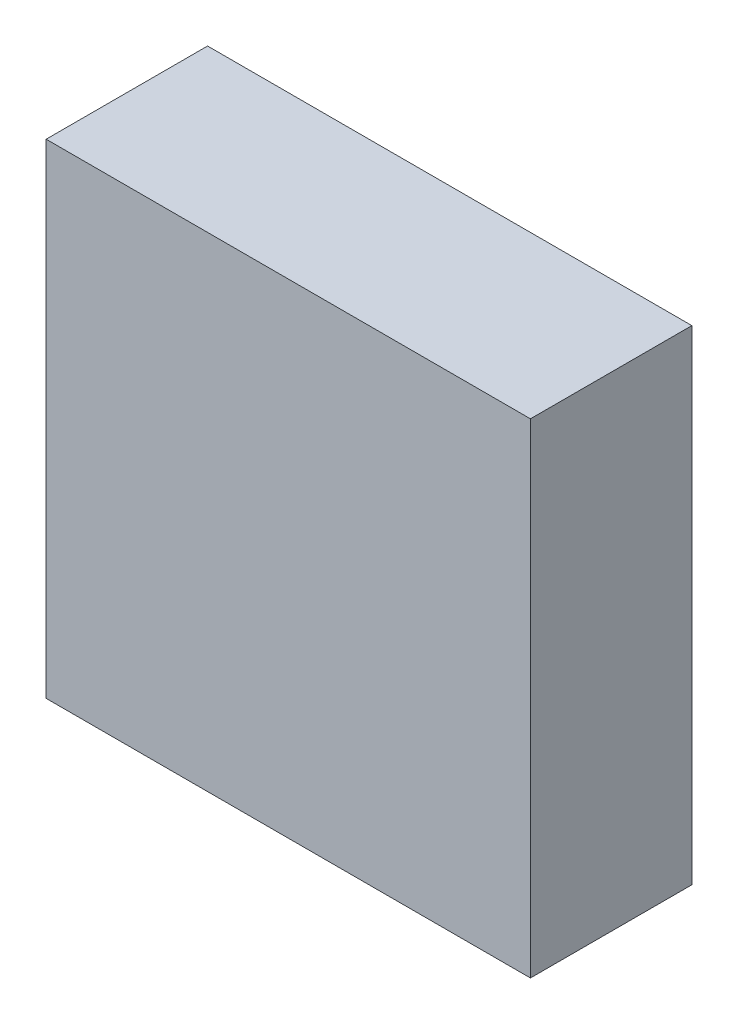
SolidWorks part; units mm, degrees
material "Custom Plastic"
ref_plane "Front Plane" through (0, 0, 0) normal (0, 0, 1) x (1, 0, 0)
ref_plane "Top Plane" through (0, 0, 0) normal (0, 1, 0) x (1, 0, 0)
ref_plane "Right Plane" through (0, 0, 0) normal (1, 0, 0) x (0, 0, -1)
sketch "Sketch1" plane through (0, 0, 0) normal (0, 0, 1) x (1, 0, 0)
  line L1 (-228.1977, 20.7849) -> (71.8023, 20.7849)
  line L2 (-228.1977, 20.7849) -> (-228.1977, -279.2151)
  line L3 (-228.1977, -279.2151) -> (71.8023, -279.2151)
  line L4 (71.8023, 20.7849) -> (71.8023, -279.2151)
  dimension "D1" = 300
  dimension "D2" = 300
extrude "Boss-Extrude1" add sketch "Sketch1" along normal blind 100
